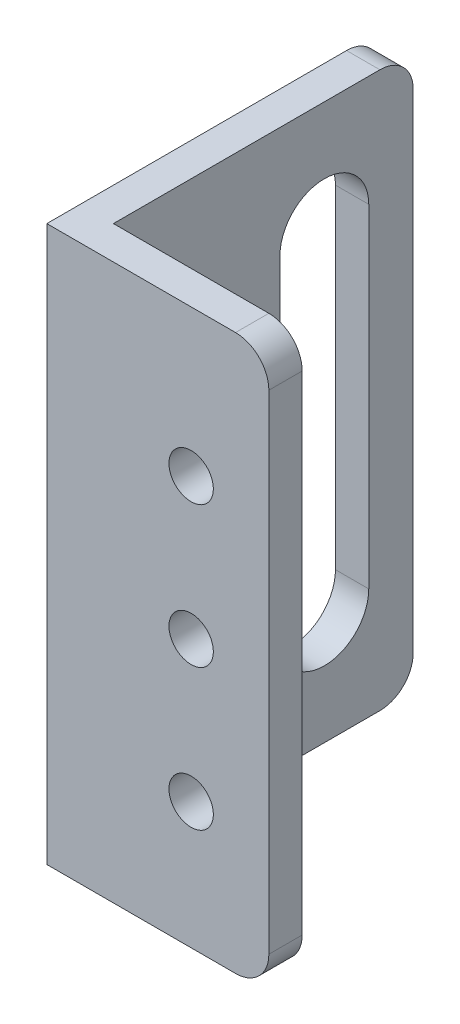
SolidWorks part; units mm, degrees
ref_plane "前视基准面" through (0, 0, 0) normal (0, 0, 1) x (1, 0, 0)
ref_plane "上视基准面" through (0, 0, 0) normal (0, 1, 0) x (1, 0, 0)
ref_plane "右视基准面" through (0, 0, 0) normal (1, 0, 0) x (0, 0, -1)
sketch "草图1" plane through (0, 0, 0) normal (0, 1, 0) x (1, 0, 0)
  line L2 (-1.5, 15) -> (1.5, 15)
  line L3 (-1.5, 15) -> (-1.5, -15)
  line L4 (-1.5, -15) -> (1.5, -15)
  line L5 (1.5, 15) -> (1.5, -15)
  line L6 (-1.5, 15) -> (1.5, -15) construction
  line L7 (-1.5, -15) -> (1.5, 15) construction
  line L8 (-1.5, -15) -> (18.5, -15)
  line L9 (-1.5, -15) -> (-1.5, -12)
  line L10 (-1.5, -12) -> (18.5, -12)
  line L11 (18.5, -15) -> (18.5, -12)
  point P2 (0, 0)
  dimension "D1" = 3
  dimension "D2" = 3
  dimension "D3" = 30
  dimension "D4" = 20
extrude "凸台-拉伸1" add sketch "草图1" along normal blind 50 contours L3 L10 L5 L2 | L10 L3 L4 L5 | L8 L11 L10 L5
sketch "草图2" plane through (0, 0, 15) normal (0, 0, 1) x (1, 0, 0)
  line L0 (11.5, 50) -> (11.5, 0) construction
  line L1 (-1.5, 50) -> (18.5, 50) construction
  line L3 (18.5, 50) -> (18.5, 0) construction
  circle A0 centre (11.5, 36.8) radius 2
  circle A2 centre (11.5, 24.1) radius 2
  circle A3 centre (11.5, 11.4) radius 2
  dimension "D1" = 4
  dimension "D2" = 13.2
  dimension "D4" = 12.7
  dimension "D5" = 7
  dimension "D3" = 3
extrude "切除-拉伸1" cut sketch "草图2" against normal blind 10
sketch "草图3" plane through (-1.5, 0, 0) normal (-1, 0, 0) x (0, 0, 1)
  line L0 (-7, 40) -> (-7, 10) construction
  line L1 (-3, 40) -> (-3, 10)
  line L2 (-11, 40) -> (-11, 10)
  line L4 (-15, 50) -> (-15, 0) construction
  line L5 (-15, 25) -> (15, 25) construction
  line L6 (15, 50) -> (15, 0) construction
  arc A0 (-3, 40) -> (-11, 40) centre (-7, 40) ccw
  arc A1 (-11, 10) -> (-3, 10) centre (-7, 10) ccw
  point P3 (-7, 25)
  dimension "D3" = 4
  dimension "D1" = 30
  dimension "D2" = 8
extrude "切除-拉伸2" cut sketch "草图3" against normal blind 10
fillet "圆角1" radius 3 4 edges at (18.5, 0, 13.5) (18.5, 50, 13.5) (0, 0, -15) (0, 50, -15)
